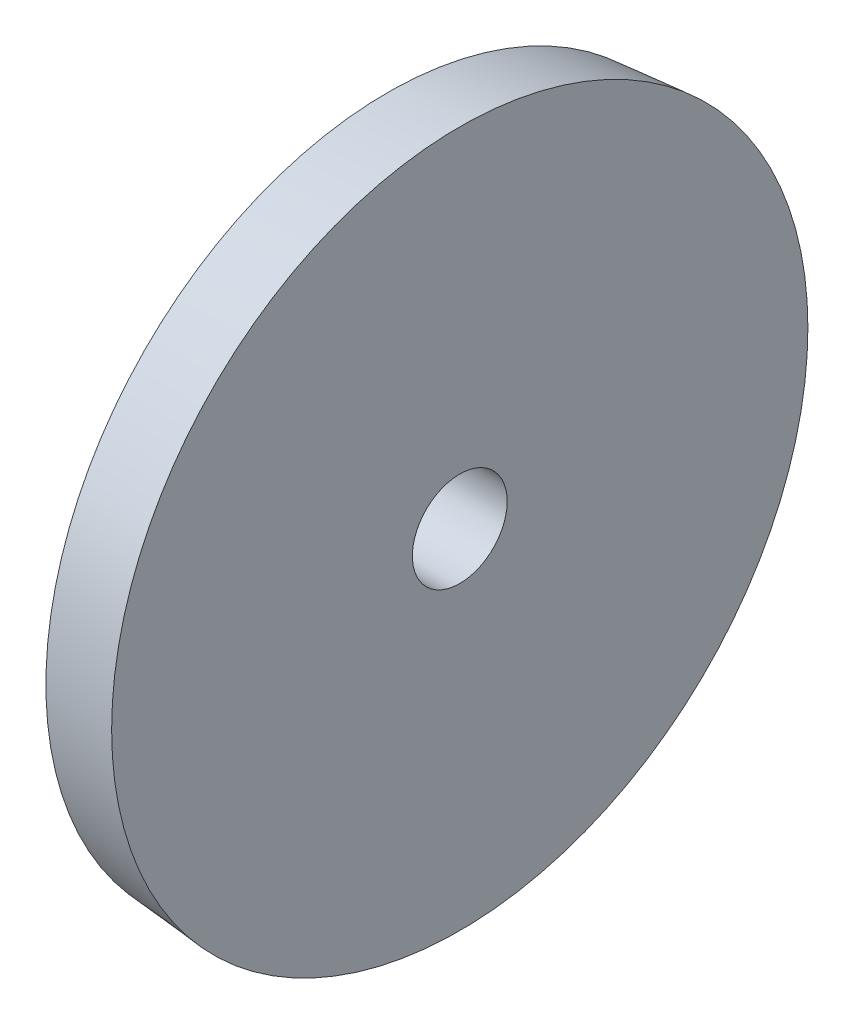
SolidWorks part; units mm, degrees
ref_plane "Front Plane" through (0, 0, 0) normal (1, 0, 0) x (0, 1, 0)
ref_plane "Top Plane" through (0, 0, 0) normal (0, 0, 1) x (0, 1, 0)
ref_plane "Right Plane" through (0, 0, 0) normal (0, 1, 0) x (-1, 0, 0)
sketch "Sketch2" plane through (0, 0, 0) normal (0, 0, 1) x (0, 1, 0)
  line L0 (0, 0) -> (0, 7.62) construction
  line L1 (5.0165, 0) -> (36.83, 0)
  line L2 (36.83, 0) -> (36.1633, 7.62)
  line L3 (36.1633, 7.62) -> (5.0165, 7.62)
  line L4 (5.0165, 7.62) -> (5.0165, 0)
  dimension "D1" = 5.0165
  dimension "D2" = 36.83
  dimension "D3" = 5
  dimension "D4" = 7.62
revolve "Revolve1" add sketch "Sketch2" angle 360 about L0
